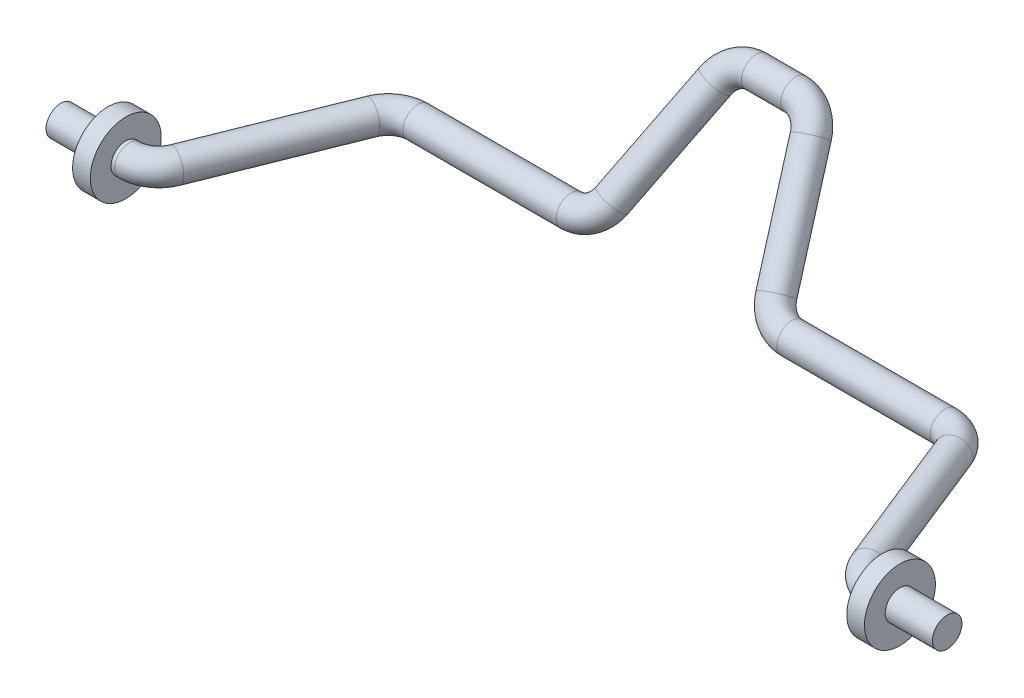
SolidWorks part; units mm, degrees
ref_plane "Front Plane" through (0, 0, 0) normal (0, 0, 1) x (1, 0, 0)
ref_plane "Top Plane" through (0, 0, 0) normal (0, 1, 0) x (1, 0, 0)
ref_plane "Right Plane" through (0, 0, 0) normal (1, 0, 0) x (0, 0, -1)
sketch3d "3DSketch1"
  line L0 (0, 0, 0) -> (0, 20, -16) construction
  line L1 (0, 20, -16) -> (-3.3235, 20, -16)
  line L2 (-75, 0, 30) -> (-63.3852, 0, 30)
  line L3 (-58.7428, 0, 26.857) -> (-49.2572, 0, 3.143)
  line L4 (-44.6148, 0, 0) -> (-18.6765, 0, 0)
  line L5 (-13.9039, 2.7403, -2.1922) -> (-8.0961, 17.2597, -13.8078)
  arc A0 (-3.3235, 20, -16) -> (-8.0961, 17.2597, -13.8078) centre (-3.3235, 16.0957, -12.8765) ccw
  arc A1 (-18.6765, 0, 0) -> (-13.9039, 2.7403, -2.1922) centre (-18.6765, 3.9043, -3.1235) ccw
  arc A2 (-49.2572, 0, 3.143) -> (-44.6148, 0, 0) centre (-44.6148, 0, 5) ccw
  arc A3 (-63.3852, 0, 30) -> (-58.7428, 0, 26.857) centre (-63.3852, 0, 25) ccw
  point P10 (-7, 20, -16)
  point P11 (-3.3235, 19.2191, -8.9722)
  point P14 (-15, 0, 0)
  point P15 (-18.6765, 7.0278, 0.7809)
  point P18 (-48, 0, 0)
  point P19 (-44.6148, -5, 5)
  point P22 (-60, 0, 30)
  point P23 (-63.3852, 5, 25)
  point P24 (0, 20, -16)
  dimension "D9" = 5
  dimension "D1" = 16
  dimension "D2" = 20
  dimension "D3" = 7
  dimension "D4" = 15
  dimension "D5" = 60
  dimension "D6" = 48
  dimension "D7" = 15
  dimension "D8" = 30
sketch "Sketch1" plane through (0, 0, 0) normal (1, 0, 0) x (0, 0, -1)
  circle A0 centre (16, 20) radius 2.5
  dimension "D1" = 5
sweep "Sweep1" add profiles "Sketch1" path "3DSketch1"
ref_plane "Plane1" through (-67, 0, 0) normal (-1, 0, 0) x (0, 0, 1)
sketch "Sketch3" plane through (-67, 0, 0) normal (-1, 0, 0) x (0, 0, 1)
  circle A0 centre (30, 0) radius 6
  dimension "D1" = 12
extrude "Boss-Extrude1" add sketch "Sketch3" against normal blind 3
mirror "Mirror1" about plane through (0, 20, -16) normal (1, 0, 0) of bodies 107
